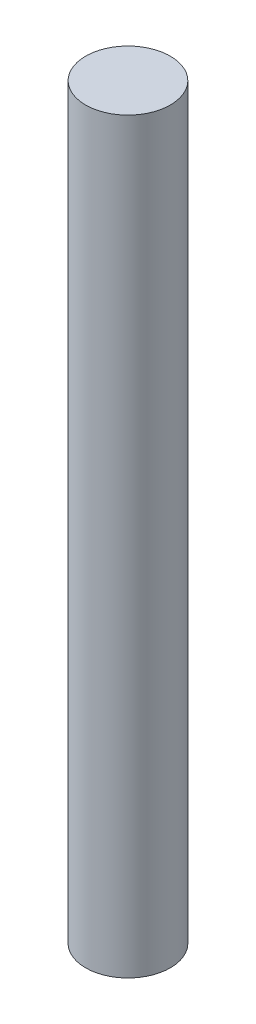
SolidWorks part; units mm, degrees
ref_plane "Front Plane" through (0, 0, 0) normal (0, 0, 1) x (1, 0, 0)
ref_plane "Top Plane" through (0, 0, 0) normal (0, 1, 0) x (1, 0, 0)
ref_plane "Right Plane" through (0, 0, 0) normal (1, 0, 0) x (0, 0, -1)
sketch "Sketch1" plane through (0, 0, 0) normal (0, 1, 0) x (1, 0, 0)
  line L0 (47.2297, 219.0186) -> (732.563, 219.0186) construction
  circle A0 centre (-1.6248, 18.0734) radius 1.7
extrude "Boss-Extrude1" add sketch "Sketch1" along normal blind 30
